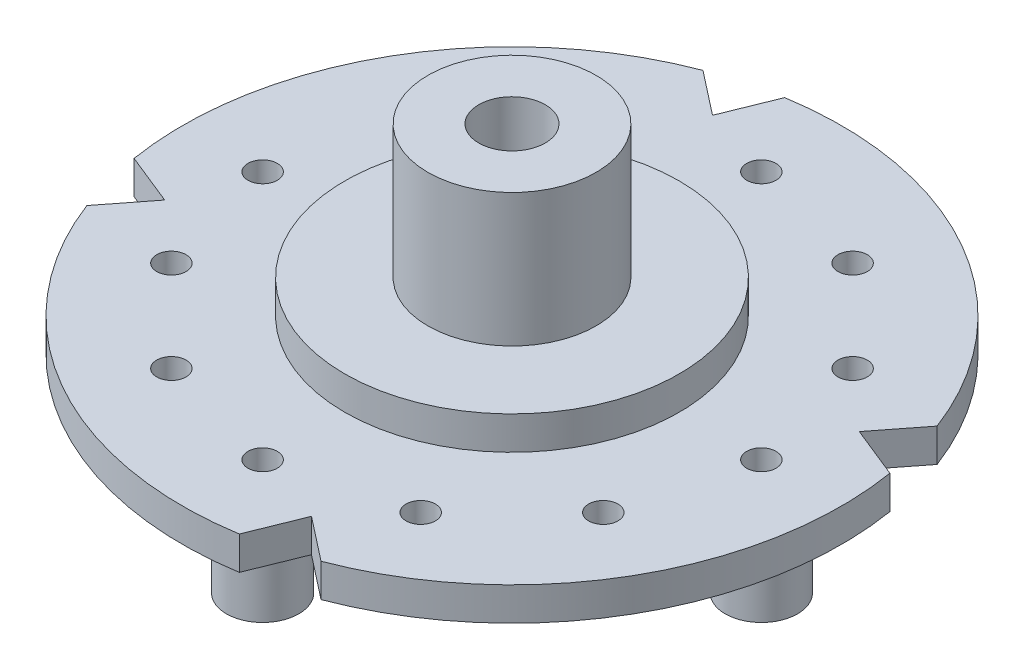
SolidWorks part; units mm, degrees
ref_plane "Front Plane" through (0, 0, 0) normal (0, 0, 1) x (1, 0, 0)
ref_plane "Top Plane" through (0, 0, 0) normal (0, 1, 0) x (1, 0, 0)
ref_plane "Right Plane" through (0, 0, 0) normal (1, 0, 0) x (0, 0, -1)
sketch "Sketch1" plane through (0, 0, 0) normal (0, 0, 1) x (1, 0, 0)
  line L0 (0, 0) -> (-42.799, 0)
  line L1 (-42.799, 0) -> (-42.799, 4.318)
  line L2 (-42.799, 4.318) -> (-21.717, 4.318)
  line L3 (-21.717, 4.318) -> (-21.717, 8.636)
  line L4 (-21.717, 8.636) -> (-10.922, 8.636)
  line L5 (-10.922, 8.636) -> (-10.922, 25.908)
  line L6 (-10.922, 25.908) -> (0, 25.908)
  line L7 (0, 25.908) -> (0, 0)
  line L8 (0, 25.908) -> (0, -23.737) construction
  line L10 (0, 25.908) -> (-4.318, 25.908)
  line L11 (0, 25.908) -> (0, 4.572)
  line L12 (0, 4.572) -> (-4.318, 4.572)
  line L13 (-4.318, 25.908) -> (-4.318, 4.572)
  dimension "D1" = 4.318
  dimension "D2" = 17.272
  dimension "D3" = 4.318
  dimension "D4" = 21.844
  dimension "D5" = 43.434
  dimension "D6" = 85.598
  dimension "D7" = 8.636
  dimension "D8" = 21.336
revolve "Revolve1" add sketch "Sketch1" angle 360 about L8
sketch "Sketch4" plane through (0, 0, 0) normal (0, -1, 0) x (1, 0, 0)
  line L0 (-51.9571, 0) -> (65.9326, 0) construction
  circle A0 centre (0, 32.385) radius 4.699
  circle A1 centre (32.385, 0) radius 4.699
  circle A2 centre (0, -32.385) radius 4.699
  circle A3 centre (-32.385, 0) radius 4.699
  point P14 (0, 0)
  dimension "D2" = 9.398
  dimension "D1" = 32.385
  dimension "D3" = 4
extrude "Boss-Extrude1" add sketch "Sketch4" along normal blind 10.668
sketch "Sketch2" plane through (0, 4.318, 0) normal (0, 1, 0) x (1, 0, 0)
  line L0 (-60.9755, 0) -> (52.3768, 0) construction
  circle A0 centre (-32.385, 0) radius 1.905
  circle A1 centre (-28.0462, 16.1925) radius 1.905
  circle A2 centre (-16.1925, 28.0462) radius 1.905
  circle A3 centre (0, 32.385) radius 1.905
  circle A4 centre (16.1925, 28.0462) radius 1.905
  circle A5 centre (28.0462, 16.1925) radius 1.905
  circle A6 centre (32.385, 0) radius 1.905
  circle A7 centre (28.0462, -16.1925) radius 1.905
  circle A8 centre (16.1925, -28.0462) radius 1.905
  circle A9 centre (0, -32.385) radius 1.905
  circle A10 centre (-16.1925, -28.0462) radius 1.905
  circle A11 centre (-28.0462, -16.1925) radius 1.905
  point P5 (-32.385, 0)
  point P28 (0, 0)
  dimension "D2" = 3.81
  dimension "D1" = 32.385
  dimension "D3" = 12
extrude "Cut-Extrude1" cut sketch "Sketch2" against normal through all
sketch "Sketch3" plane through (0, 0, 0) normal (0, -1, 0) x (1, 0, 0)
  line L0 (0, 42.799) -> (0, -45.0258) construction
  line L1 (6.8356, 42.2496) -> (9.5323, 35.575)
  line L2 (35.575, -9.5323) -> (40.007, -15.205)
  line L3 (9.5323, 35.575) -> (15.205, 40.007)
  line L4 (42.2496, -6.8356) -> (35.575, -9.5323)
  line L5 (0, 0) -> (82.4219, 0) construction
  line L6 (16.3853, 61.1508) -> (-14.305, -53.3872) construction
  line L7 (-9.5323, -35.575) -> (-15.205, -40.007)
  line L8 (-6.8356, -42.2496) -> (-9.5323, -35.575)
  line L9 (-35.575, 9.5323) -> (-40.007, 15.205)
  line L10 (-42.2496, 6.8356) -> (-35.575, 9.5323)
  circle A0 centre (0, 0) radius 42.799 construction
  arc A1 (0, 42.799) -> (0, -42.799) centre (0, 0) ccw
  arc A2 (15.205, 40.007) -> (6.8356, 42.2496) centre (0, 0) ccw
  arc A3 (40.007, -15.205) -> (42.2496, -6.8356) centre (0, 0) ccw
  arc A4 (-15.205, -40.007) -> (-6.8356, -42.2496) centre (0, 0) ccw
  arc A5 (-40.007, 15.205) -> (-42.2496, 6.8356) centre (0, 0) ccw
  point P24 (0, 0)
  circle M14 centre (0, 0) radius 42.799
  dimension "D1" = 74
  dimension "D2" = 36.83
  dimension "D3" = 75
  dimension "D4" = 4
extrude "Cut-Extrude2" cut sketch "Sketch3" against normal through all contours L10 L9 M14 | L1 L3 M14 | L4 L2 M14 | L8 L7 M14
